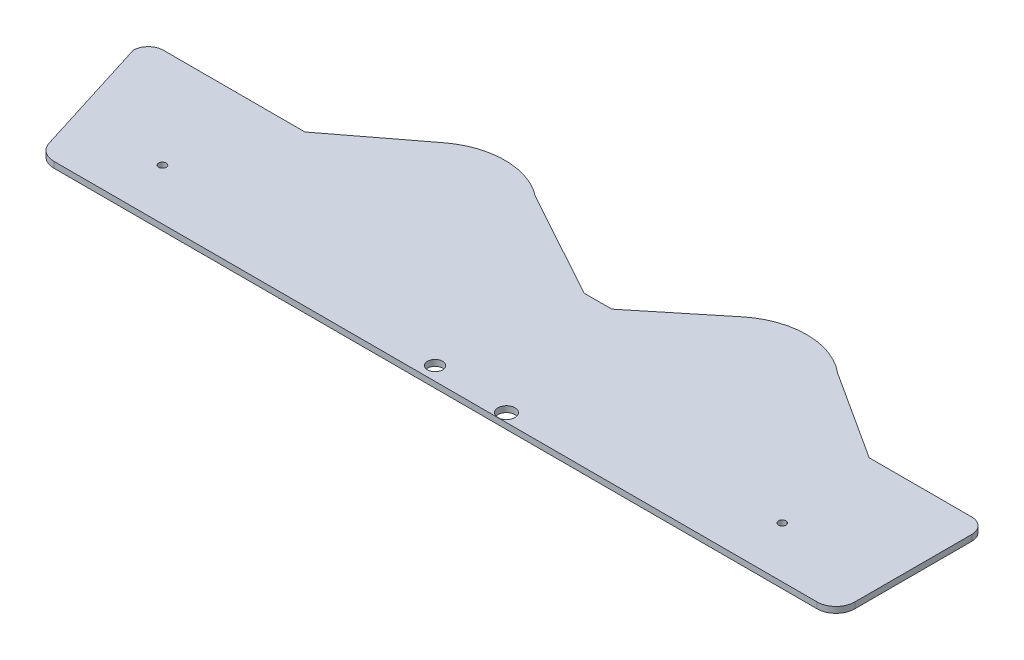
SolidWorks part; units mm, degrees
ref_plane "Front" through (0, 0, 0) normal (0, 0, 1) x (1, 0, 0)
ref_plane "Top" through (0, 0, 0) normal (0, 1, 0) x (1, 0, 0)
ref_plane "Right" through (0, 0, 0) normal (1, 0, 0) x (0, 0, -1)
sketch "Sketch1" plane through (0, 0, 0) normal (0, 1, 0) x (1, 0, 0)
  line L0 (0, 142) -> (42, 8)
  line L1 (0, 0) -> (444.5, 0)
  line L2 (0, 0) -> (0, 150)
  line L3 (0, 150) -> (444.5, 150)
  line L4 (444.5, 0) -> (444.5, 150)
  circle A0 centre (8, 142) radius 8
  circle A1 centre (50, 8) radius 8
  circle A2 centre (436.5, 142) radius 8
  circle A3 centre (436.5, 8) radius 8
  circle A4 centre (265.2813, 74.5639) radius 4.5112
  circle A5 centre (146.2694, 139.8404) radius 3.7162
  circle A6 centre (307.6065, 140.7106) radius 4.3136
  dimension "D3" = 8
  dimension "D5" = 8
  dimension "D7" = 8
  dimension "D9" = 8
  dimension "D1" = 150
  dimension "D2" = 444.5
  dimension "D4" = 8
  dimension "D6" = 50
  dimension "D8" = 8
  dimension "D10" = 8
extrude "Boss-Extrude1" add sketch "Sketch1" along normal blind 3.175 contours A3 L4 A2 L3 A0 L0 A1 L1 | A1 | A0 L0 | A2 | A3
sketch "Sketch2" plane through (0, 0, 0) normal (0, 0, 1) x (1, 0, 0)
  line L1 (-78.5546, 38.0306) -> (518.9117, 38.0306)
  line L2 (-78.5546, 38.0306) -> (-78.5546, -22.9419)
  line L3 (-78.5546, -22.9419) -> (518.9117, -22.9419)
  line L4 (518.9117, 38.0306) -> (518.9117, -22.9419)
extrude "Cut-Extrude1" cut sketch "Sketch2" against normal blind 70
fillet "Fillet1" radius 10 1 edges at (22.5672, 1.5875, -70)
fillet "Fillet2" radius 10 1 edges at (444.5, 1.5875, -70)
sketch "Sketch3" plane through (0, 3.175, 0) normal (0, 1, 0) x (1, 0, 0)
  line L0 (444.5, 80) -> (444.5, 142) construction
  line L1 (29.9125, 70) -> (434.5, 70) construction
  circle A0 centre (224.75, 77.255) radius 3.9908
  dimension "D1" = 219.75
  dimension "D2" = 7.255
extrude "Cut-Extrude2" cut sketch "Sketch3" against normal blind 10
sketch "Sketch4" plane through (0, 3.175, 0) normal (0, 1, 0) x (1, 0, 0)
  line L0 (29.9125, 70) -> (434.5, 70) construction
  line L1 (444.5, 80) -> (444.5, 142) construction
  circle A0 centre (60.5, 97) radius 2
  dimension "D3" = 4
  dimension "D1" = 27
  dimension "D2" = 384
extrude "Cut-Extrude3" cut sketch "Sketch4" against normal through all
sketch "Sketch5" plane through (0, 3.175, 0) normal (0, 1, 0) x (1, 0, 0)
  line L0 (444.5, 80) -> (444.5, 142) construction
  line L1 (29.9125, 70) -> (434.5, 70) construction
  circle A0 centre (389, 97) radius 2
  dimension "D1" = 55.5
  dimension "D3" = 4
  dimension "D2" = 27
extrude "Cut-Extrude4" cut sketch "Sketch5" against normal blind 10
sketch "Sketch6" plane through (0, 0, 0) normal (0, 1, 0) x (1, 0, 0)
  circle A0 centre (149, 150.0404) radius 40
  dimension "D1" = 80
  dimension "D2" = 141
extrude "Boss-Extrude2" add sketch "Sketch6" along normal blind 3.175
sketch "Sketch7" plane through (0, 0, 0) normal (0, 1, 0) x (1, 0, 0)
  line L0 (124.1645, 181.3964) -> (82.7029, 149.7505)
  line L1 (173.8355, 181.3964) -> (231.4689, 149.7505)
  line L2 (82.7029, 149.7505) -> (231.4689, 149.7505)
  line L3 (124.1645, 181.3964) -> (173.8355, 181.3964)
  arc A0 (189, 150) -> (109, 150) centre (149, 150.0404) ccw construction
extrude "Boss-Extrude3" add sketch "Sketch7" along normal blind 3.175
sketch "Sketch9" plane through (0, 0, 0) normal (0, 1, 0) x (1, 0, 0)
  line L0 (444.5, 80) -> (444.5, 142) construction
  line L1 (231.0146, 150) -> (436.5, 150) construction
  line L2 (283.7342, 181.0103) -> (245.6734, 150)
  line L3 (245.6734, 150) -> (269, 150)
  line L4 (334.2658, 181.0103) -> (397.5744, 150)
  circle A0 centre (309, 150) radius 40
  dimension "D1" = 135.5
  dimension "D2" = 0
extrude "Boss-Extrude4" add sketch "Sketch9" along normal blind 3.175 contours A0 L2 L3 | A0
sketch "Sketch12" plane through (0, 0, 0) normal (0, 1, 0) x (1, 0, 0)
  line L0 (326.1663, 186.1292) -> (382.1065, 150)
  line L1 (349, 150) -> (436.5, 150) construction
  line L2 (382.1065, 150) -> (340.3988, 150)
  line L3 (340.3988, 150) -> (326.1663, 186.1292)
  arc A0 (349, 150) -> (283.7342, 181.0103) centre (309, 150) ccw construction
extrude "Boss-Extrude6" add sketch "Sketch12" along normal blind 3.175
sketch "Sketch14" plane through (0, 3.175, 0) normal (0, 1, 0) x (1, 0, 0)
  circle A0 centre (140, 139.2404) radius 6.619
  arc A1 (8, 150) -> (0, 142) centre (8, 142) ccw construction
  arc A2 (173.8355, 181.3964) -> (124.1645, 181.3964) centre (149, 150.0404) ccw construction
  point P8 (149, 190.0404)
  dimension "D2" = 50.8
  dimension "D1" = 132
